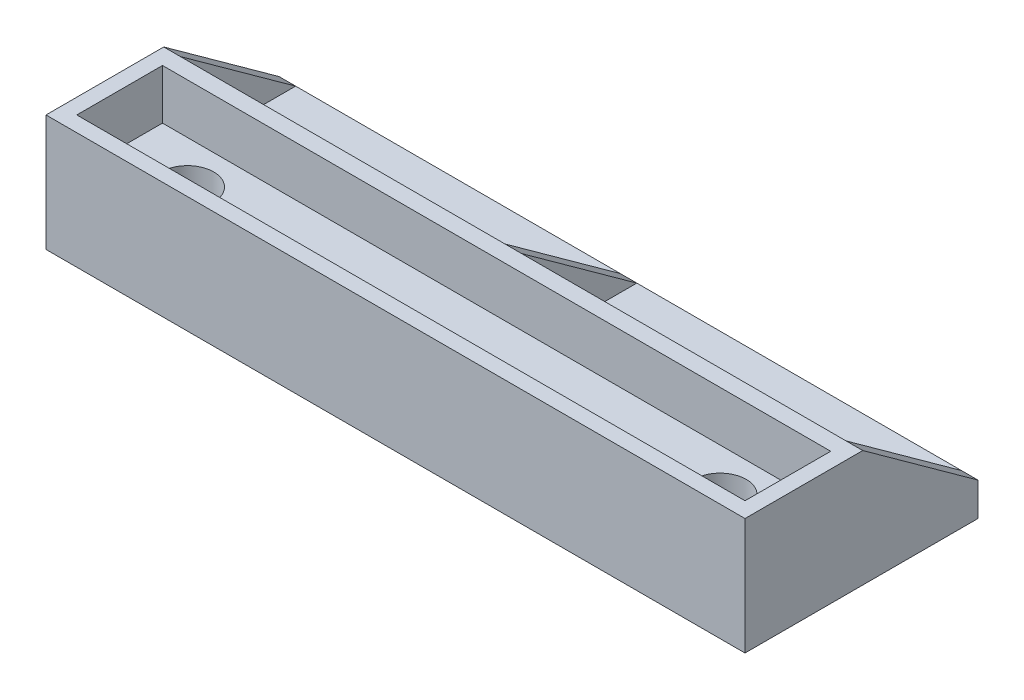
SolidWorks part; units mm, degrees
ref_plane "Front Plane" through (0, 0, 0) normal (0, 0, 1) x (1, 0, 0)
ref_plane "Top Plane" through (0, 0, 0) normal (0, 1, 0) x (1, 0, 0)
ref_plane "Right Plane" through (0, 0, 0) normal (1, 0, 0) x (0, 0, -1)
sketch "Sketch1" plane through (0, 0, 0) normal (0, 1, 0) x (1, 0, 0)
  line L1 (0, 7) -> (42, 7)
  line L2 (0, 7) -> (0, 0)
  line L3 (0, 0) -> (42, 0)
  line L4 (42, 7) -> (42, 0)
  dimension "D2" = 42
  dimension "D3" = 7
extrude "Riser" add sketch "Sketch1" along normal blind 7
sketch "Sketch2" plane through (0, 0, 0) normal (0, -1, 0) x (1, 0, 0)
  line L0 (0, -7) -> (0, 0) construction
  line L1 (21, 0) -> (21, -7) construction
  line L2 (0, 0) -> (42, 0) construction
  line L4 (42, -7) -> (0, -7) construction
  circle A2 centre (5, -3.5) radius 1.575
  circle A3 centre (37, -3.5) radius 1.575
  point P2 (0, -3.5)
  dimension "D2" = 3.15
  dimension "D1" = 5
extrude "Mounting Holes" cut sketch "Sketch2" against normal through all
sketch "Sketch3" plane through (0, 7, 0) normal (0, 1, 0) x (1, 0, 0)
  line L12 (0.925, 6.075) -> (41.075, 6.075)
  line L13 (0.925, 6.075) -> (0.925, 0.925)
  line L14 (0.925, 0.925) -> (41.075, 0.925)
  line L15 (41.075, 6.075) -> (41.075, 0.925)
  line L17 (0, 7) -> (0, 0) construction
  line L18 (42, 7) -> (0, 7) construction
  dimension "D1" = 5.15
  dimension "D2" = 40.15
  dimension "D3" = 0.925
  dimension "D4" = 0.925
extrude "Recess" cut sketch "Sketch3" against normal blind 3 contours L12 L15 L14 L13
sketch "Sketch4" plane through (0, 0, 0) normal (0, 1, 0) x (1, 0, 0)
  line L1 (0, 7) -> (42, 7)
  line L2 (42, 7) -> (42, 14)
  line L3 (42, 14) -> (0, 14)
  line L4 (0, 14) -> (0, 7)
  dimension "D1" = 7
extrude "Flange" add sketch "Sketch4" along normal blind 7
sketch "Sketch5" plane through (0, 7, 0) normal (0, 1, 0) x (1, 0, 0)
  line L0 (1, 7.075) -> (1, 14)
  line L1 (42, 14) -> (0, 14) construction
  line L2 (1, 14) -> (20.5, 14)
  line L3 (20.5, 14) -> (20.5, 7.075)
  line L4 (20.5, 7.075) -> (1, 7.075)
  line L7 (42, 14) -> (0, 14) construction
  line L8 (21.5, 14) -> (41, 14)
  line L11 (0, 14) -> (0, 0) construction
  line L12 (0.925, 6.075) -> (41.075, 6.075) construction
  line L17 (21.5, 14) -> (21.5, 7.075)
  line L18 (21.5, 7.075) -> (41, 7.075)
  line L19 (41, 14) -> (41, 7.075)
  line L20 (42, 0) -> (42, 14) construction
  dimension "D1" = 1
  dimension "D2" = 1
  dimension "D3" = 1
  dimension "D4" = 1
  dimension "D5" = 19.5
extrude "Flange Cutout" cut sketch "Sketch5" against normal blind 5
sketch "Sketch7" plane through (20.5, 0, 0) normal (-1, 0, 0) x (0, 0, 1)
  line L0 (-7.075, 7) -> (-14, 2)
  line L1 (-14, 2) -> (-14, 7)
  line L2 (-14, 7) -> (-7.075, 7)
extrude "Angle Cutout" cut sketch "Sketch7" against normal through all and the other way through all
chamfer "Flange Chamfer 1" distance 1 angle 45 1 edges at (10.75, 2, -7.075)
chamfer "Flange Chamfer 2" distance 1 angle 45 1 edges at (31.25, 2, -7.075)
